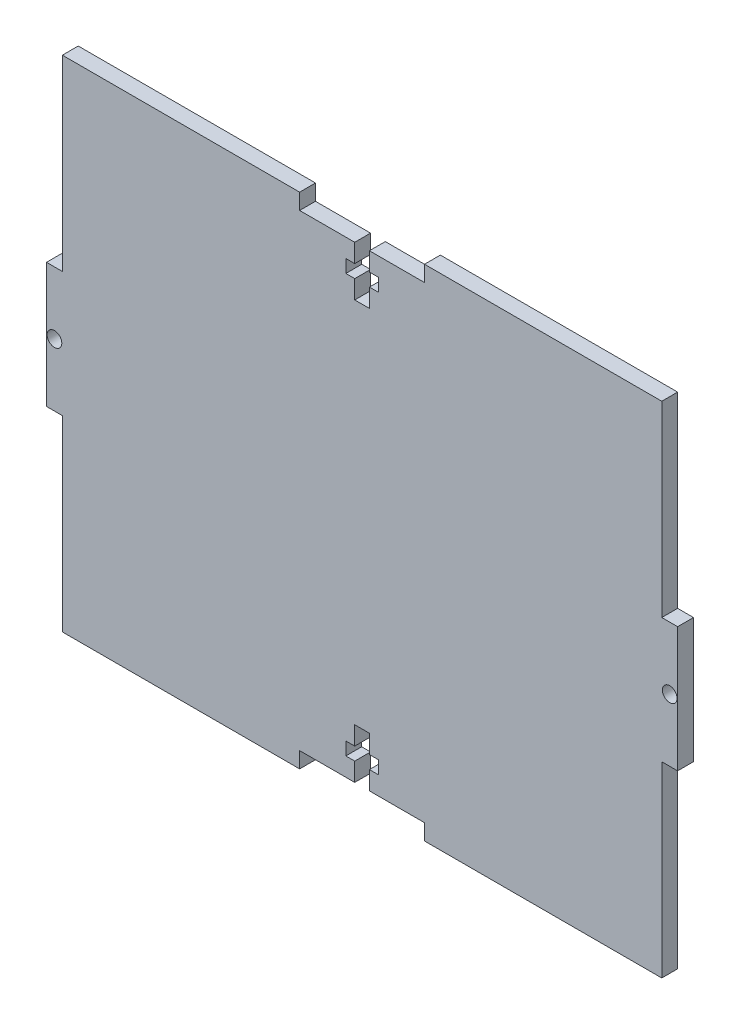
SolidWorks part; units mm, degrees
ref_plane "Front Plane" through (0, 0, 0) normal (0, 0, 1) x (1, 0, 0)
ref_plane "Top Plane" through (0, 0, 0) normal (0, 1, 0) x (1, 0, 0)
ref_plane "Right Plane" through (0, 0, 0) normal (1, 0, 0) x (0, 0, -1)
sketch "Sketch1" plane through (0, 0, 0) normal (0, 0, 1) x (1, 0, 0)
  line L0 (0, 50) -> (0, -50) construction
  line L1 (-60, 50) -> (60, 50)
  line L2 (-60, 50) -> (-60, -50)
  line L3 (-60, -50) -> (60, -50)
  line L4 (60, 50) -> (60, -50)
  line L5 (-60, 50) -> (60, -50) construction
  line L6 (-60, -50) -> (60, 50) construction
  line L7 (-60, 0) -> (60, 0) construction
  line L8 (-3.25, -40.525) -> (3.25, -40.525)
  line L9 (12.5, 50) -> (-12.5, 50)
  line L10 (12.5, 50) -> (12.5, 46.825)
  line L11 (12.5, 46.825) -> (-12.5, 46.825)
  line L12 (-12.5, 50) -> (-12.5, 46.825)
  line L13 (12.5, 50) -> (-12.5, 46.825) construction
  line L14 (12.5, 46.825) -> (-12.5, 50) construction
  line L15 (-1.47, 46.825) -> (1.47, 46.825)
  line L16 (-1.47, 46.825) -> (-1.47, 36.825)
  line L17 (-1.47, 36.825) -> (1.47, 36.825)
  line L18 (1.47, 46.825) -> (1.47, 36.825)
  line L19 (-1.47, 46.825) -> (1.47, 36.825) construction
  line L20 (-1.47, 36.825) -> (1.47, 46.825) construction
  line L21 (-3.25, 43.125) -> (3.25, 43.125)
  line L22 (-3.25, 43.125) -> (-3.25, 40.525)
  line L23 (-3.25, 40.525) -> (3.25, 40.525)
  line L24 (3.25, 43.125) -> (3.25, 40.525)
  line L25 (-3.25, 43.125) -> (3.25, 40.525) construction
  line L26 (-3.25, 40.525) -> (3.25, 43.125) construction
  line L27 (3.25, -43.125) -> (3.25, -40.525)
  line L28 (-3.25, -43.125) -> (3.25, -43.125)
  line L29 (-3.25, -43.125) -> (-3.25, -40.525)
  line L30 (-1.47, -36.825) -> (1.47, -36.825)
  line L31 (1.47, -46.825) -> (1.47, -36.825)
  line L32 (-1.47, -46.825) -> (1.47, -46.825)
  line L33 (-1.47, -46.825) -> (-1.47, -36.825)
  line L34 (12.5, -46.825) -> (-12.5, -46.825)
  line L35 (-12.5, -50) -> (-12.5, -46.825)
  line L36 (12.5, -50) -> (-12.5, -50)
  line L37 (12.5, -50) -> (12.5, -46.825)
  line L38 (63.175, -12.5) -> (60, -12.5)
  line L39 (-63.175, 12.5) -> (-60, 12.5)
  line L40 (-63.175, 12.5) -> (-63.175, -12.5)
  line L41 (-63.175, -12.5) -> (-60, -12.5)
  line L42 (-60, 12.5) -> (-60, -12.5)
  line L43 (-63.175, 12.5) -> (-60, -12.5) construction
  line L44 (-63.175, -12.5) -> (-60, 12.5) construction
  line L45 (60, 12.5) -> (60, -12.5)
  line L46 (63.175, 12.5) -> (60, 12.5)
  line L47 (63.175, 12.5) -> (63.175, -12.5)
  circle A0 centre (-61.5875, 0) radius 1.47
  circle A1 centre (61.5875, 0) radius 1.47
  point P0 (0, 0)
  point P10 (0, 48.4125)
  point P15 (0, 41.825)
  point P20 (0, 41.825)
  point P37 (-61.5875, 0)
  dimension "D11" = 2.94
  dimension "D1" = 100
  dimension "D2" = 120
  dimension "D3" = 3.175
  dimension "D4" = 10
  dimension "D5" = 2.94
  dimension "D6" = 25
  dimension "D7" = 6.5
  dimension "D8" = 2.6
  dimension "D9" = 6.3
  dimension "D10" = 3.175
extrude "Boss-Extrude1" add sketch "Sketch1" along normal mid plane 3.175 contours L21 L24 L23 L18 L17 L16 L22 L11 L12 L1 L2 L3 L4 L10 | L40 L39 L42 L41 | A0 | L38 L45 L46 L47 | A1
